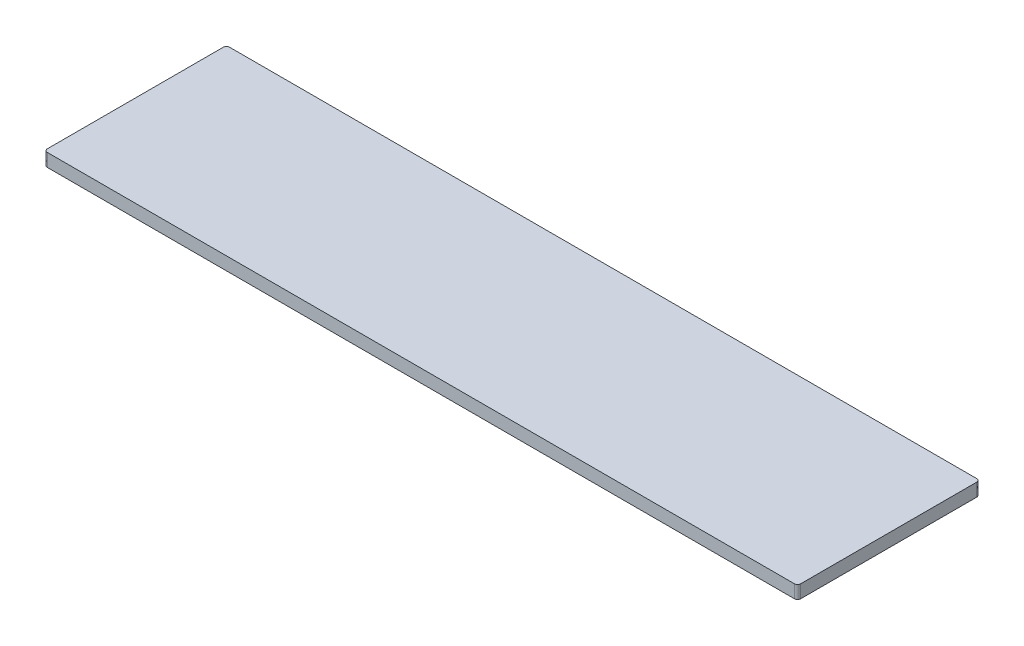
SolidWorks part; units mm, degrees
ref_plane "Front Plane" through (0, 0, 0) normal (0, 0, 1) x (1, 0, 0)
ref_plane "Top Plane" through (0, 0, 0) normal (0, 1, 0) x (1, 0, 0)
ref_plane "Right Plane" through (0, 0, 0) normal (1, 0, 0) x (0, 0, -1)
sketch "Sketch1" plane through (0, 0, 0) normal (0, 1, 0) x (1, 0, 0)
  line L1 (-367.5, -88.9) -> (367.5, -88.9)
  line L2 (-367.5, -88.9) -> (-367.5, 88.9)
  line L3 (-367.5, 88.9) -> (367.5, 88.9)
  line L4 (367.5, -88.9) -> (367.5, 88.9)
  line L5 (-367.5, -88.9) -> (367.5, 88.9) construction
  line L6 (-367.5, 88.9) -> (367.5, -88.9) construction
  point P0 (0, 0)
  dimension "D1" = 735
  dimension "D2" = 177.8
extrude "Boss-Extrude1" add sketch "Sketch1" along normal blind 12.7
fillet "Fillet1" radius 3 4 edges at (-367.5, 6.35, 88.9) (-367.5, 6.35, -88.9) (367.5, 6.35, -88.9) (367.5, 6.35, 88.9)
